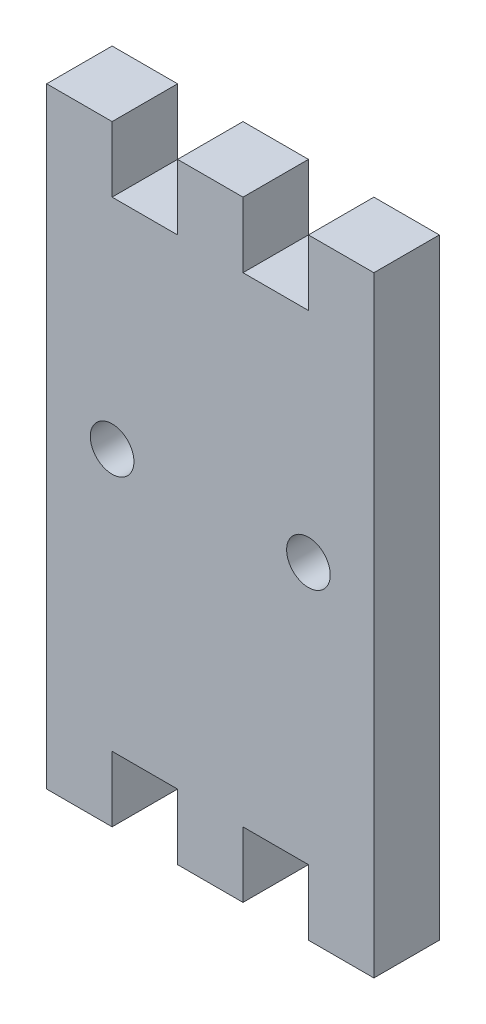
SolidWorks part; units mm, degrees
ref_plane "Front Plane" through (0, 0, 0) normal (0, 0, 1) x (1, 0, 0)
ref_plane "Top Plane" through (0, 0, 0) normal (0, 1, 0) x (1, 0, 0)
ref_plane "Right Plane" through (0, 0, 0) normal (1, 0, 0) x (0, 0, -1)
sketch "Sketch1" plane through (0, 0, 0) normal (0, 0, 1) x (1, 0, 0)
  line L0 (0, 14) -> (0, -14) construction
  line L5 (-7.5, -14) -> (-4.5, -14)
  line L6 (-7.5, -14) -> (-7.5, 14)
  line L7 (-7.5, 14) -> (-4.5, 14)
  line L8 (7.5, -14) -> (7.5, 14)
  line L9 (-7.5, -14) -> (7.5, 14) construction
  line L10 (-7.5, 14) -> (7.5, -14) construction
  line L14 (-4.5, 14) -> (-4.5, 11)
  line L15 (-4.5, 11) -> (-1.5, 11)
  line L16 (-1.5, 14) -> (-1.5, 11)
  line L17 (-4.5, 14) -> (-1.5, 11) construction
  line L18 (-4.5, 11) -> (-1.5, 14) construction
  line L19 (4.5, 11) -> (1.5, 11)
  line L20 (1.5, 14) -> (1.5, 11)
  line L22 (4.5, 14) -> (4.5, 11)
  line L23 (-1.5, 14) -> (1.5, 14)
  line L24 (4.5, 14) -> (7.5, 14)
  line L25 (-1.5, -14) -> (1.5, -14)
  line L26 (-4.5, -11) -> (-1.5, -11)
  line L27 (-4.5, -11) -> (-4.5, -14)
  line L29 (-1.5, -11) -> (-1.5, -14)
  line L30 (4.5, -14) -> (7.5, -14)
  line L31 (1.5, -11) -> (4.5, -11)
  line L32 (1.5, -11) -> (1.5, -14)
  line L34 (4.5, -11) -> (4.5, -14)
  circle A2 centre (-4.5, 1) radius 1
  circle A4 centre (4.5, 1) radius 1
  point P0 (0, 0)
  point P11 (-3, 12.5)
  point P29 (0, 0)
  dimension "D8" = 3
  dimension "D9" = 3
  dimension "D4" = 10
  dimension "D5" = 4.5
  dimension "D3" = 2
  dimension "D1" = 15
  dimension "D2" = 28
  dimension "D6" = 3
  dimension "D7" = 3
  dimension "D10" = 3
  dimension "D11" = 3
  dimension "D12" = 3
  dimension "D13" = 3
  dimension "D14" = 4.5
  dimension "D15" = 3
extrude "Boss-Extrude2" add sketch "Sketch1" along normal blind 3
